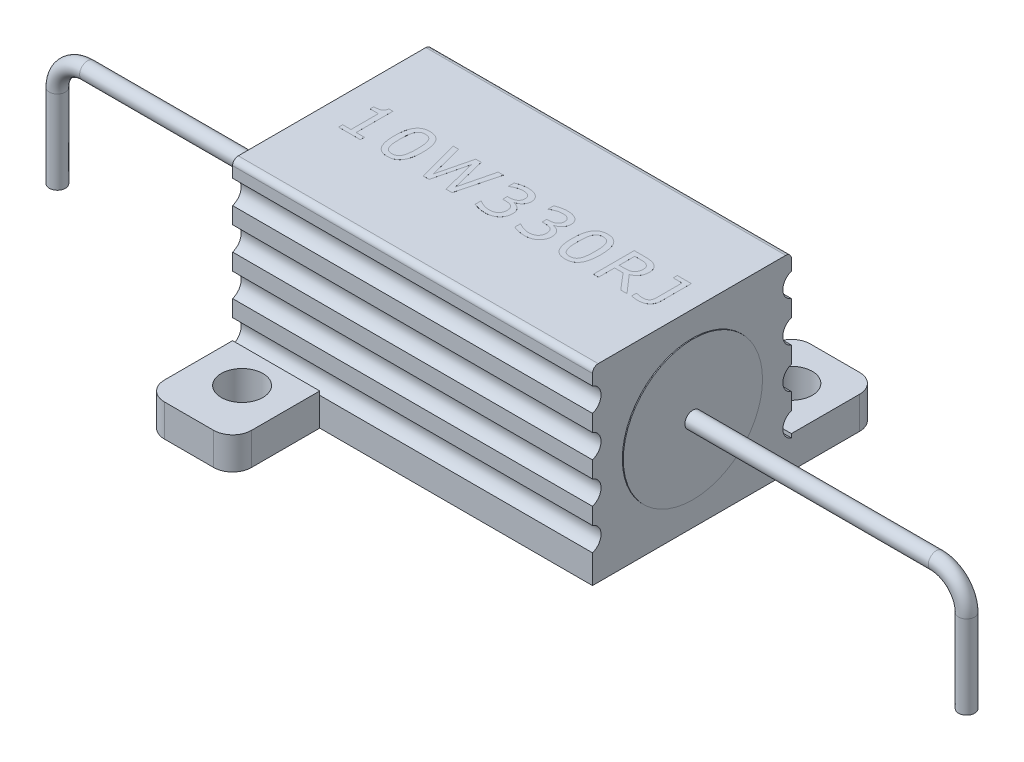
SolidWorks part; units mm, degrees
material "2024-T4"
ref_plane "Front Plane" through (0, 0, 0) normal (0, 0, 1) x (1, 0, 0)
ref_plane "Top Plane" through (0, 0, 0) normal (0, 1, 0) x (1, 0, 0)
ref_plane "Right Plane" through (0, 0, 0) normal (1, 0, 0) x (0, 0, -1)
sketch "Sketch1" plane through (0, 0, 0) normal (1, 0, 0) x (0, 0, -1)
  line L0 (-4.8, 3.5) -> (-4.8, 2.2804) construction
  line L1 (-4.95, 5) -> (4.95, 5)
  line L2 (-5.25, 5) -> (-5.25, -5) construction
  line L3 (-5.25, -5) -> (5.25, -5)
  line L4 (5.25, 4.7) -> (5.25, 4.125)
  line L5 (-5.25, 5) -> (5.25, -5) construction
  line L6 (-5.25, -5) -> (5.25, 5) construction
  line L7 (-5.25, 4.7) -> (-5.25, 4.125)
  line L8 (-5.25, 2.875) -> (-5.25, 2)
  line L9 (-5.25, 0.75) -> (-5.25, -0.125)
  line L10 (-5.25, -1.375) -> (-5.25, -2.25)
  line L11 (-5.25, -3.5) -> (-5.25, -5)
  line L12 (0, 0) -> (0, -1.597) construction
  line L13 (5.25, 4.125) -> (5.25, 2.875) construction
  line L14 (5.25, 2.875) -> (5.25, 2)
  line L15 (5.25, 2) -> (5.25, 0.75) construction
  line L16 (5.25, 0.75) -> (5.25, -0.125)
  line L17 (5.25, -0.125) -> (5.25, -1.375) construction
  line L18 (5.25, -1.375) -> (5.25, -2.25)
  line L19 (5.25, -2.25) -> (5.25, -3.5) construction
  line L20 (5.25, -3.5) -> (5.25, -5)
  arc A0 (-5.25, 4.125) -> (-5.25, 2.875) centre (-5.459, 3.5) cw
  arc A1 (-5.25, 2) -> (-5.25, 0.75) centre (-5.459, 1.375) cw
  arc A2 (-5.25, -0.125) -> (-5.25, -1.375) centre (-5.459, -0.75) cw
  arc A3 (-5.25, -2.25) -> (-5.25, -3.5) centre (-5.459, -2.875) cw
  arc A4 (5.25, -2.25) -> (5.25, -3.5) centre (5.459, -2.875) ccw
  arc A5 (5.25, -0.125) -> (5.25, -1.375) centre (5.459, -0.75) ccw
  arc A6 (5.25, 4.125) -> (5.25, 2.875) centre (5.459, 3.5) ccw
  arc A7 (5.25, 2) -> (5.25, 0.75) centre (5.459, 1.375) ccw
  arc A8 (4.95, 5) -> (5.25, 4.7) centre (4.95, 4.7) cw
  arc A9 (-4.95, 5) -> (-5.25, 4.7) centre (-4.95, 4.7) ccw
  point P0 (0, 0)
  dimension "D3" = 4.8
  dimension "D8" = 0.3
  dimension "D1" = 10
  dimension "D2" = 10.5
  dimension "D4" = 1.5
  dimension "D5" = 1.25
  dimension "D7" = 1.5
  dimension "D6" = 4
extrude "Boss-Extrude1" add sketch "Sketch1" along normal mid plane 19
sketch "Sketch2" plane through (0, -5, 0) normal (0, -1, 0) x (1, 0, 0)
  line L5 (0, 0) -> (13.2167, 0) construction
  line L6 (0, 7.9538) -> (0, -6.2812) construction
  line L16 (-7.2, -11.3006) -> (-7.2, -4.0961) construction
  line L17 (-10.7974, -7.55) -> (-3.5315, -7.55) construction
  line L18 (9.5, -5.25) -> (-9.5, -5.25) construction
  line L19 (-4.9, 8.85) -> (-4.9, 5.25)
  line L20 (-8.5, 9.85) -> (-5.9, 9.85)
  line L21 (-9.5, 5.25) -> (-9.5, 8.85)
  line L22 (-4.9, 5.25) -> (-9.5, 5.25)
  line L23 (4.9, -8.85) -> (4.9, -5.25)
  line L24 (4.9, -5.25) -> (9.5, -5.25)
  line L25 (9.5, -5.25) -> (9.5, -8.85)
  line L26 (8.5, -9.85) -> (5.9, -9.85)
  circle A9 centre (-7.2, 7.05) radius 1.1
  arc A10 (-4.9, 8.85) -> (-5.9, 9.85) centre (-5.9, 8.85) ccw
  arc A11 (-9.5, 8.85) -> (-8.5, 9.85) centre (-8.5, 8.85) cw
  circle A12 centre (7.2, -7.55) radius 1.1
  arc A13 (9.5, -8.85) -> (8.5, -9.85) centre (8.5, -8.85) cw
  arc A14 (4.9, -8.85) -> (5.9, -9.85) centre (5.9, -8.85) ccw
  point P13 (4.9, 9.85)
  point P16 (9.5, 9.85)
  point P50 (-4.9, -9.85)
  point P51 (-9.5, -9.85)
  dimension "D2" = 4.6
  dimension "D7" = 2.3
extrude "Boss-Extrude2" add sketch "Sketch2" against normal blind 1.7
sketch "Sketch3" plane through (0, 0, 0) normal (1, 0, 0) x (0, 0, -1)
  circle A0 centre (0, 0) radius 3.675
  dimension "D1" = 7.35
extrude "Boss-Extrude3" add sketch "Sketch3" along normal mid plane 19.1
sketch "Sketch5" plane through (0, 0, 0) normal (1, 0, 0) x (0, 0, -1)
  circle A0 centre (0, 0) radius 1
  dimension "D1" = 2
extrude "Boss-Extrude4" [suppressed] add sketch "Sketch5" along normal mid plane 48
sketch "Sketch6" [suppressed] plane through (0, 0, 0) normal (0, 0, 1) x (1, 0, 0)
  line L0 (24, -1) -> (24, 1) construction
  line L1 (-15.6066, 0) -> (23.2797, 0) construction
  line L2 (24, 1) -> (24, 5.1151) construction
  line L3 (27.9, 0) -> (27.9, 5.4523) construction
  line L4 (10.6512, 1) -> (24, 1) construction
  line L5 (24, 1) -> (9.55, 1) construction
  line L6 (0, 8.4055) -> (0, -7.6743) construction
  line L7 (24, 1) -> (24, -1)
  arc A0 (24, 1) -> (26.433, 1.85) centre (27.9164, -6.3031) cw
  arc A1 (26.433, 1.85) -> (26.433, -1.85) centre (26, 0) cw
  arc A2 (24, -1) -> (26.433, -1.85) centre (27.9164, 6.3031) ccw
  circle A3 centre (26, 0) radius 1.1649
  dimension "D1" = 3.9
  dimension "D3" = 27.9
  dimension "D2" = 3.7
  dimension "D4" = 2
extrude "Boss-Extrude5" [suppressed] add sketch "Sketch6" along normal mid plane 0.9
mirror "Mirror1" [suppressed] about plane through (0, 0, 0) normal (1, 0, 0)
fillet "Fillet1" [suppressed] radius 1
sketch "Sketch7" plane through (0, 5, 0) normal (0, 1, 0) x (1, 0, 0)
  line L0 (9.5, 0) -> (-9.5, 0) construction
  line L1 (9.5, 4.95) -> (9.5, -4.95) construction
  line L2 (-9.5, 4.95) -> (-9.5, -4.95) construction
  line L3 (9.5, -0.9912) -> (-9.5, -0.9912) construction
  line L4 (9.5, -2.3734) -> (-9.5, -2.3734) construction
  text T0 "10W330RJ\r\n" font "Verdana" height in points 8
extrude "Boss-Extrude6" add sketch "Sketch7" along normal blind 0.001
sketch "Sketch9" plane through (0, 0, 0) normal (0, 0, 1) x (1, 0, 0)
  line L0 (-22.4, 0) -> (22.4, 0)
  line L1 (24, -1.6) -> (24, -6)
  line L2 (0, 0) -> (0, 10.716) construction
  line L3 (-24, -1.6) -> (-24, -6)
  arc A0 (22.4, 0) -> (24, -1.6) centre (22.4, -1.6) cw
  arc A1 (-24, -1.6) -> (-22.4, 0) centre (-22.4, -1.6) cw
  point P4 (0, 0)
  point P11 (24, 0)
  point P14 (-24, 0)
  dimension "D2" = 1.6
  dimension "D1" = 6
  dimension "D3" = 48
sweep "Sweep1" add path "Sketch9" circular profile diameter 0.85 parameters "D3"=0.85
